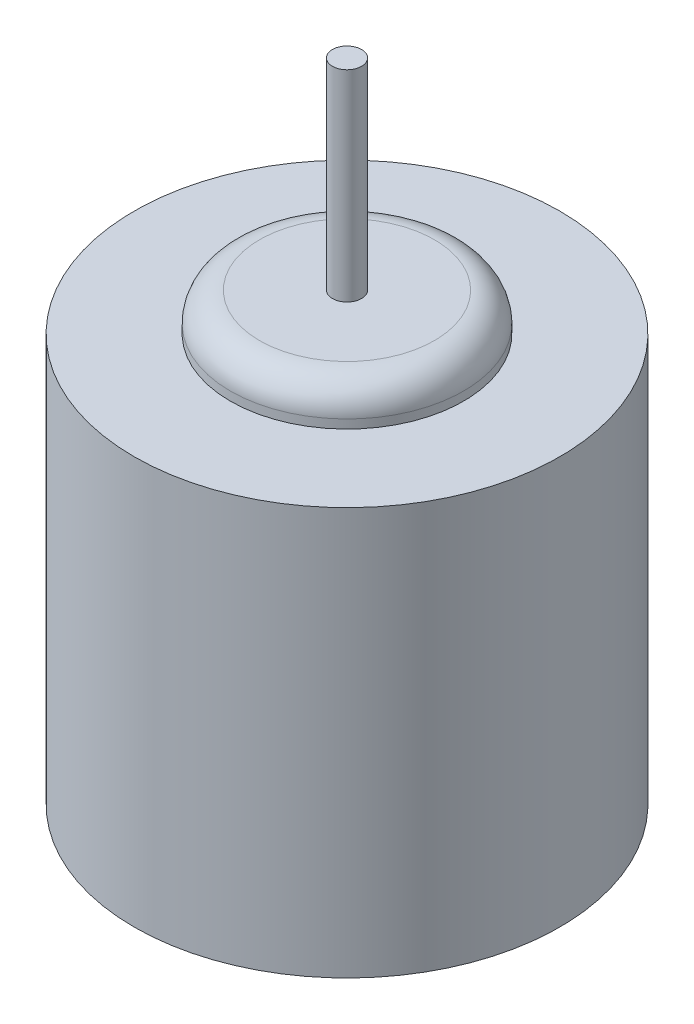
SolidWorks part; units mm, degrees
ref_plane "前基準面" through (0, 0, 0) normal (0, 0, 1) x (1, 0, 0)
ref_plane "上基準面" through (0, 0, 0) normal (0, 1, 0) x (1, 0, 0)
ref_plane "右基準面" through (0, 0, 0) normal (1, 0, 0) x (0, 0, -1)
sketch "草圖1" plane through (0, 0, 0) normal (0, 1, 0) x (1, 0, 0)
  circle A0 centre (0, 0) radius 14.6
  dimension "D1" = 29.2
extrude "填料-伸長1" add sketch "草圖1" along normal blind 27.95
sketch "草圖2" plane through (0, 27.95, 0) normal (0, 1, 0) x (1, 0, 0)
  circle A0 centre (0, 0) radius 8
  dimension "D1" = 16
extrude "填料-伸長2" add sketch "草圖2" along normal blind 2.6
fillet "圓角1" radius 2 1 edges at (0, 30.55, 8)
sketch "草圖3" plane through (0, 30.55, 0) normal (0, 1, 0) x (1, 0, 0)
  circle A0 centre (0, 0) radius 1
  dimension "D1" = 2
extrude "填料-伸長3" add sketch "草圖3" along normal blind 13.8
